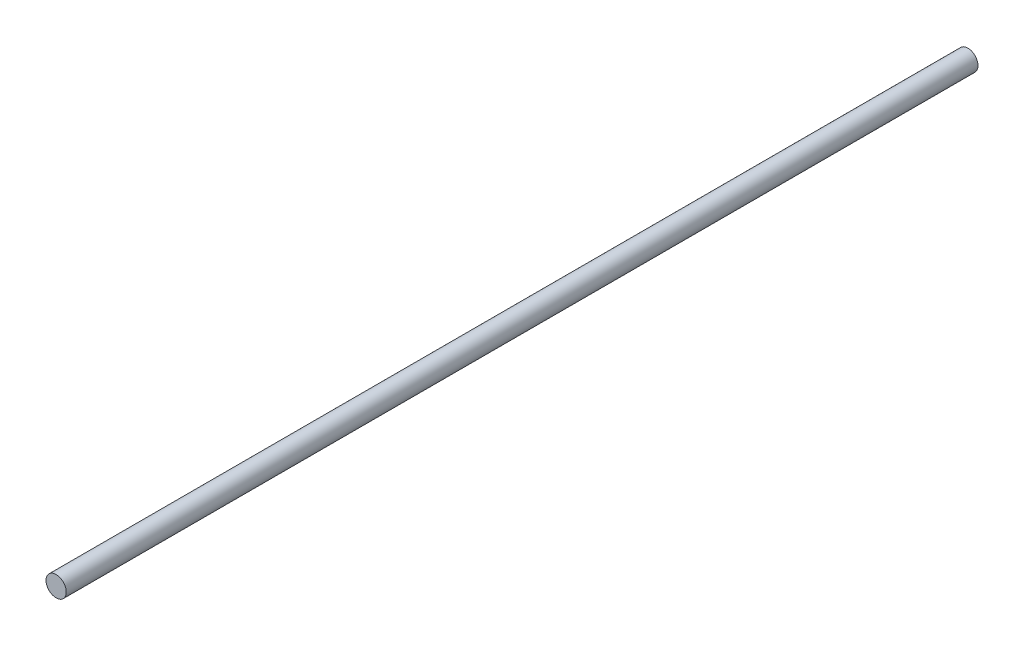
SolidWorks part; units mm, degrees
ref_plane "前视基准面" through (0, 0, 0) normal (0, 0, 1) x (1, 0, 0)
ref_plane "上视基准面" through (0, 0, 0) normal (0, 1, 0) x (1, 0, 0)
ref_plane "右视基准面" through (0, 0, 0) normal (1, 0, 0) x (0, 0, -1)
sketch "草图1" plane through (0, 0, 0) normal (0, 0, 1) x (1, 0, 0)
  circle A0 centre (0, 0) radius 4
extrude "凸台-拉伸1" add sketch "草图1" along normal blind 360
ref_plane "基准面4" through (0, 0, 180) normal (0, 0, 1) x (1, 0, 0)
